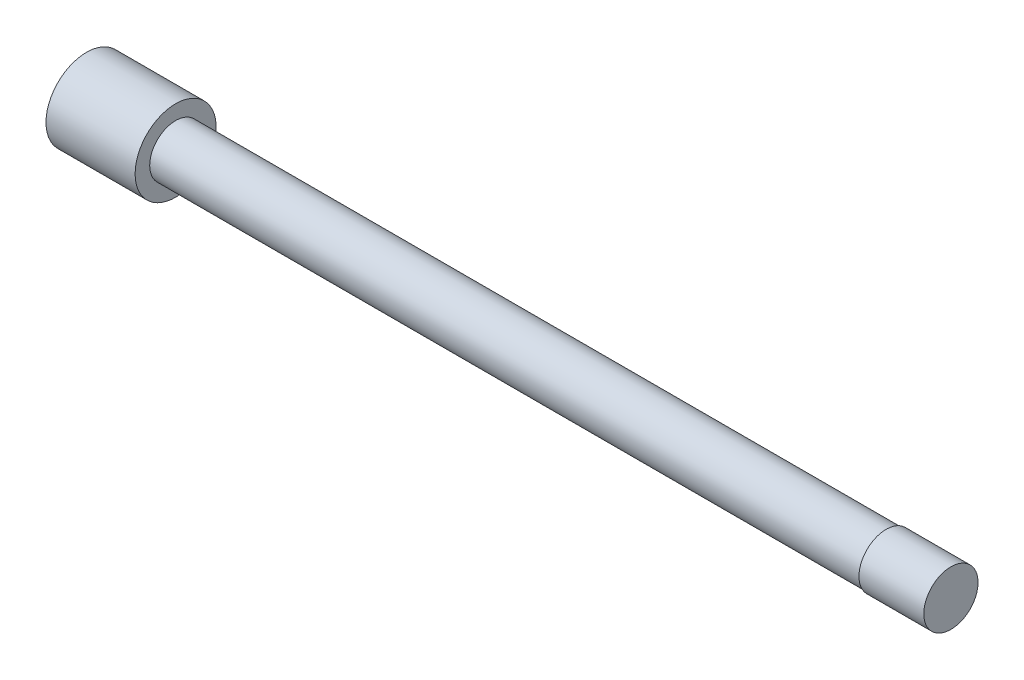
SolidWorks part; units mm, degrees
material "Copper"
ref_plane "Front Plane" through (0, 0, 0) normal (0, 0, 1) x (1, 0, 0)
ref_plane "Top Plane" through (0, 0, 0) normal (0, 1, 0) x (1, 0, 0)
ref_plane "Right Plane" through (0, 0, 0) normal (1, 0, 0) x (0, 0, -1)
sketch "Axial profile (mm)" plane through (0, 0, 0) normal (0, 0, 1) x (1, 0, 0)
  line L0 (-110, 0) -> (75, 0) construction
  line L1 (50, 3.25) -> (58, 3.25)
  line L2 (58, 3.25) -> (58, 0)
  line L3 (58, 0) -> (156.7, 0)
  line L4 (156.7, 0) -> (156.7, 3.35)
  line L5 (156.7, 3.35) -> (148.7, 3.35)
  line L6 (148.7, 3.35) -> (148.7, 3.2)
  line L7 (148.7, 3.2) -> (61, 3.2)
  line L8 (61, 3.2) -> (61, 5)
  line L9 (61, 5) -> (50, 5)
  line L10 (50, 5) -> (50, 3.25)
revolve "Full revolution" add sketch "Axial profile (mm)" angle 360 about L0
